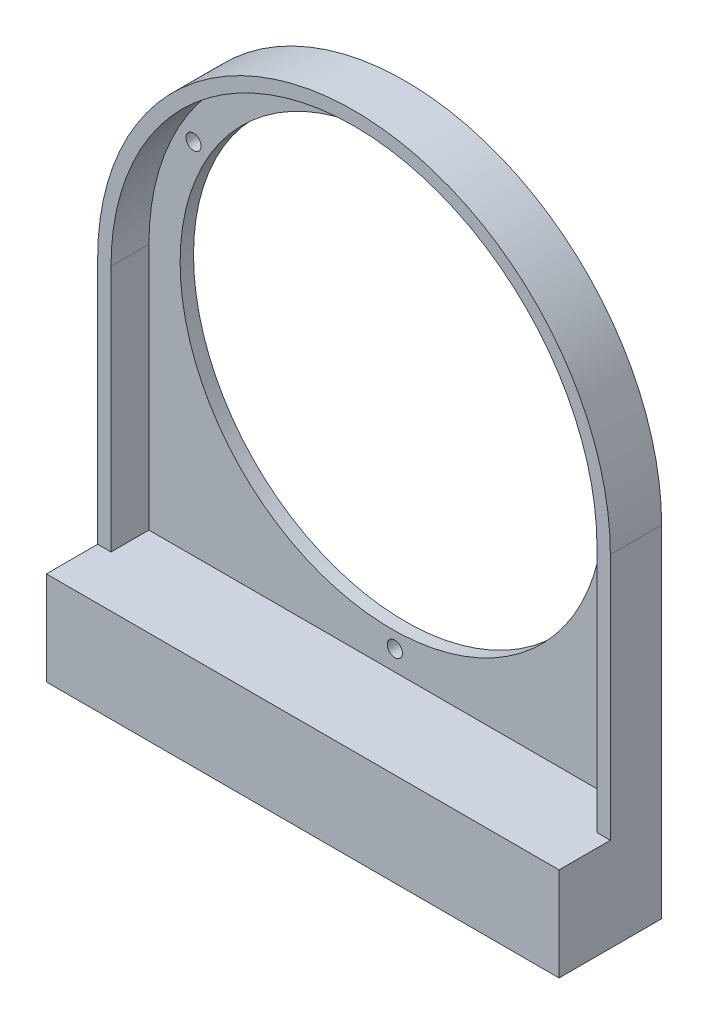
SolidWorks part; units mm, degrees
ref_plane "Plan de face" through (0, 0, 0) normal (0, 0, 1) x (1, 0, 0)
ref_plane "Plan de dessus" through (0, 0, 0) normal (0, 1, 0) x (1, 0, 0)
ref_plane "Plan de droite" through (0, 0, 0) normal (1, 0, 0) x (0, 0, -1)
sketch "Esquisse1" plane through (0, 0, 0) normal (0, 0, 1) x (1, 0, 0)
  line L0 (57.5, 0) -> (-57.5, 0)
  line L1 (-57.5, 0) -> (-57.5, 76.5)
  line L2 (57.5, 76.5) -> (57.5, 0)
  line L4 (0, 0) -> (0, 138.7071) construction
  arc A0 (-57.5, 76.5) -> (57.5, 76.5) centre (0, 76.5) cw
  dimension "D1" = 57.5
  dimension "D2" = 76.5
extrude "Boss.-Extru.1" add sketch "Esquisse1" along normal blind 11.5
sketch "Esquisse2" plane through (0, 0, 11.5) normal (0, 0, 1) x (1, 0, 0)
  line L0 (57.5, 0) -> (57.5, 76.5) construction
  line L1 (-57.5, 0) -> (57.5, 0)
  line L2 (-57.5, 0) -> (-57.5, 21)
  line L3 (-57.5, 21) -> (57.5, 21)
  line L4 (57.5, 0) -> (57.5, 21)
  dimension "D1" = 21
extrude "Boss.-Extru.2" add sketch "Esquisse2" along normal blind 11.5
sketch "Esquisse3" plane through (0, 0, 11.5) normal (0, 0, 1) x (1, 0, 0)
  line L0 (-54.5, 21) -> (-54.5, 76.5)
  line L1 (57.5, 21) -> (-57.5, 21) construction
  line L2 (54.5, 76.5) -> (54.5, 21)
  line L3 (54.5, 21) -> (-54.5, 21)
  line L4 (57.5, 21) -> (57.5, 76.5) construction
  line L5 (-57.5, 0) -> (57.5, 0) construction
  arc A0 (-54.5, 76.5) -> (54.5, 76.5) centre (0, 76.5) cw
  dimension "D1" = 54.5
  dimension "D2" = 57.5
  dimension "D3" = 76.5
extrude "Enlèv. mat.-Extru.1" cut sketch "Esquisse3" against normal blind 8.5 contours A0 L2 L3 L0
sketch "Esquisse4" plane through (0, 0, 0) normal (0, 0, -1) x (-1, 0, 0)
  circle A0 centre (0, 76.5) radius 47.5
  arc A2 (57.5, 76.5) -> (-57.5, 76.5) centre (0, 76.5) ccw construction
  point P7 (-95.8194, 95.2594)
  dimension "D1" = 95
extrude "Enlèv. mat.-Extru.2" cut sketch "Esquisse4" against normal through all
hole_wizard "Dégagement M31" positions "Esquisse6" profile "Esquisse5" hole size "M3" standard "ISO" end condition through all
sketch "Esquisse6" plane through (0, 0, 0) normal (0, 0, -1) x (-1, 0, 0)
  point P0 (-43.8351, 102.5669)
  point P3 (44.4922, 101.4288)
  point P6 (-0.6571, 25.5042)
sketch "Esquisse5" plane through (43.8351, 102.5669, 0) normal (1, 0, 0) x (0, 1, 0)
  line L0 (0, 0) -> (0, 23)
  line L1 (0, 23) -> (1.7, 23)
  line L2 (1.7, 23) -> (1.7, 0)
  line L5 (1.7, 0) -> (0, 0)
  line L11 (0, -6.35) -> (0, 107.95) construction
  dimension "Diamètre du perçage jusqu'au prochain" = 3.4
  dimension "Profondeur du perçage jusqu'au prochain" = 23
